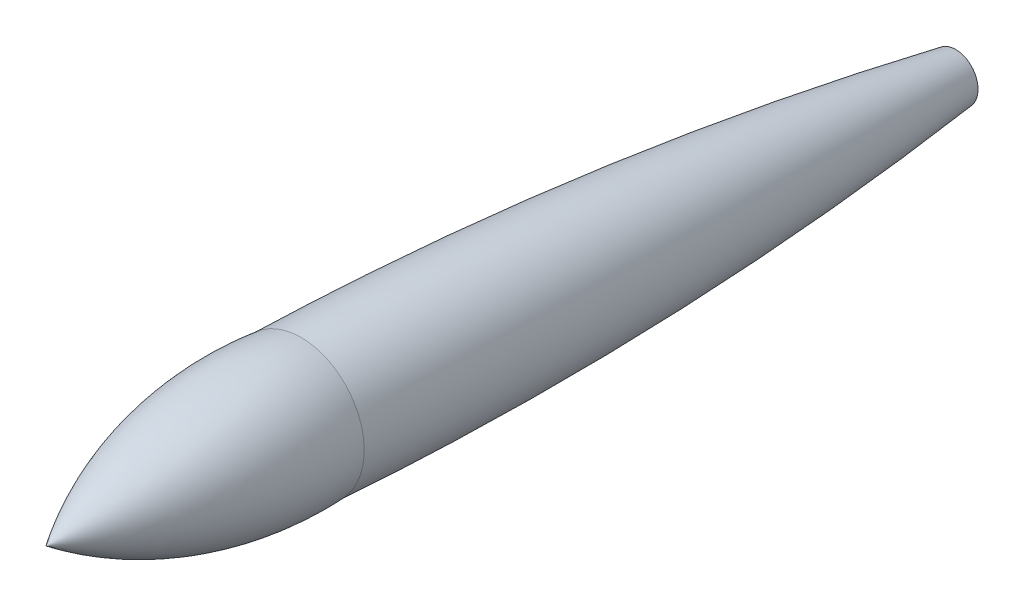
SolidWorks part; units mm, degrees
ref_plane "Front Plane" through (0, 0, 0) normal (0, 0, 1) x (1, 0, 0)
ref_plane "Top Plane" through (0, 0, 0) normal (0, 1, 0) x (1, 0, 0)
ref_plane "Right Plane" through (0, 0, 0) normal (1, 0, 0) x (0, 0, -1)
sketch "Sketch3" plane through (0, 0, 0) normal (1, 0, 0) x (0, 0, -1)
  line L0 (0, 0) -> (-102.1147, 5.4402) construction
  line L1 (0.5548, -2.6912) -> (0, 0)
  line L2 (0, 0) -> (-102.0737, 5.438)
  arc A0 (-102.0737, 5.438) -> (-74.0064, -3.5845) centre (-75.2359, 40.7578) ccw
  arc A1 (-74.0064, -3.5845) -> (0.5548, -2.6912) centre (-42.2985, 462.0038) ccw
revolve "Revolve1" add sketch "Sketch3" angle 360 about L0
